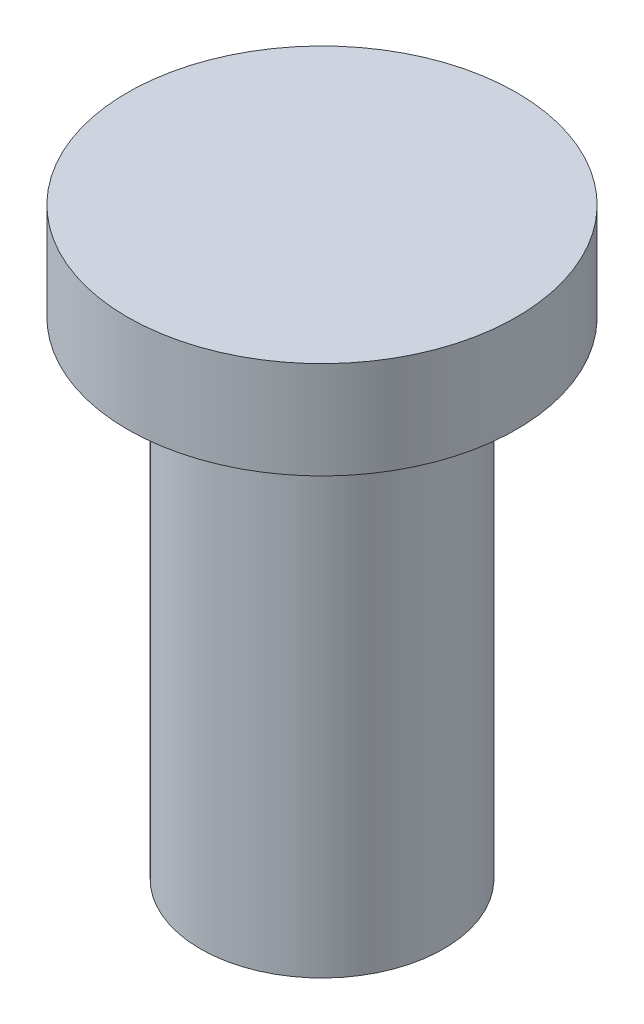
SolidWorks part; units mm, degrees
ref_plane "Front Plane" through (0, 0, 0) normal (0, 0, 1) x (1, 0, 0)
ref_plane "Top Plane" through (0, 0, 0) normal (0, 1, 0) x (1, 0, 0)
ref_plane "Right Plane" through (0, 0, 0) normal (1, 0, 0) x (0, 0, -1)
sketch "Sketch3" plane through (0, 0, 0) normal (0, 1, 0) x (1, 0, 0)
  circle A0 centre (0, 0) radius 1.25
extrude "Boss-Extrude1" add sketch "Sketch3" along normal blind 5
sketch "Sketch4" plane through (0, 5, 0) normal (0, 1, 0) x (1, 0, 0)
  circle A0 centre (0, 0) radius 2
extrude "Boss-Extrude2" add sketch "Sketch4" along normal blind 1
